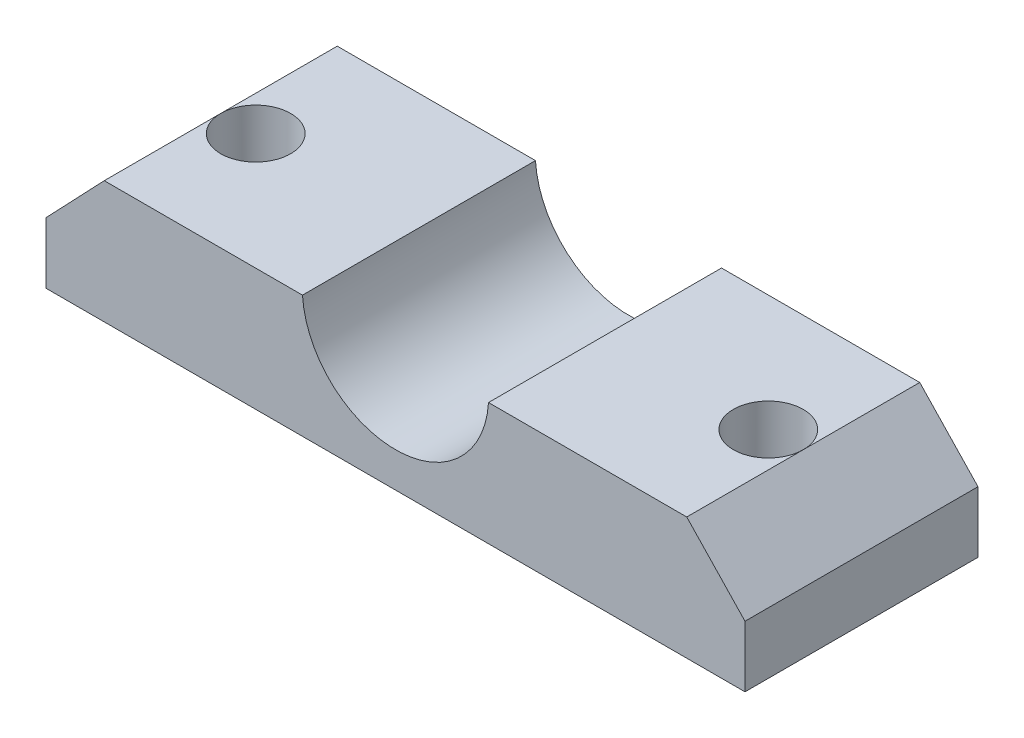
SolidWorks part; units mm, degrees
material "ABS"
ref_plane "Front Plane" through (0, 0, 0) normal (0, 0, 1) x (1, 0, 0)
ref_plane "Top Plane" through (0, 0, 0) normal (0, 1, 0) x (1, 0, 0)
ref_plane "Right Plane" through (0, 0, 0) normal (1, 0, 0) x (0, 0, -1)
sketch "Sketch1" plane through (0, 0, 0) normal (0, 0, 1) x (1, 0, 0)
  line L1 (-15, -5.5) -> (15, -5.5)
  line L2 (-15, -5.5) -> (-15, 5.5)
  line L3 (-15, 5.5) -> (15, 5.5)
  line L4 (15, -5.5) -> (15, 5.5)
  line L5 (-15, -5.5) -> (15, 5.5) construction
  line L6 (-15, 5.5) -> (15, -5.5) construction
  line L11 (-5, -5) -> (5, 5) construction
  line L12 (-5, 5) -> (5, -5) construction
  circle A0 centre (0, 0) radius 4
  point P0 (0, 0)
  point P6 (0, 0)
  dimension "D5" = 8
  dimension "D1" = 10
  dimension "D2" = 10
  dimension "D3" = 30
  dimension "D4" = 11
extrude "Boss-Extrude1" add sketch "Sketch1" along normal blind 10
sketch "Sketch2" plane through (0, 5.5, 0) normal (0, 1, 0) x (1, 0, 0)
  line L0 (0, 0) -> (0, -10)
  line L1 (15, -10) -> (-15, -10) construction
  line L2 (-11, -5) -> (11, -5)
  circle A0 centre (-11, -5) radius 1.5
  circle A1 centre (11, -5) radius 1.5
  point P8 (0, -5)
  dimension "D2" = 3
  dimension "D1" = 22
extrude "Cut-Extrude1" cut sketch "Sketch2" against normal blind 17
sketch "Sketch3" plane through (0, 0, 10) normal (0, 0, 1) x (1, 0, 0)
  line L0 (-15, 0) -> (15, 0)
  line L1 (15, -5.5) -> (15, 5.5) construction
  line L2 (-15, -0.25) -> (15, -0.25)
  line L3 (-15, 0.25) -> (15, 0.25)
  line L8 (15, -5.5) -> (15, 5.5)
  line L9 (15, 5.5) -> (-15, 5.5)
  line L10 (-15, 5.5) -> (-15, -5.5)
  line L11 (-15, -5.5) -> (15, -5.5)
  line L12 (15, -5.5) -> (15, 5.5)
  line L13 (15, 5.5) -> (-15, 5.5)
  line L14 (-15, 5.5) -> (-15, -5.5)
  line L15 (-15, -5.5) -> (15, -5.5)
  point P6 (0, 0)
  dimension "D1" = 0.25
  dimension "D2" = 0.25
  dimension "D3" = 0
extrude "Cut-Extrude2" cut sketch "Sketch3" against normal blind 17
sketch "Sketch4" plane through (0, 0, 10) normal (0, 0, 1) x (1, 0, 0)
  line L0 (11, 0) -> (-11, 0)
  line L1 (-11, 0) -> (-11, -5.5)
  line L2 (-15, -5.5) -> (15, -5.5) construction
  line L3 (11, 1.5) -> (-12.5, 1.5)
  line L4 (-12.5, 1.5) -> (-12.5, -5.5)
  line L5 (11, -1.5) -> (-9.5, -1.5)
  line L6 (-9.5, -1.5) -> (-9.5, -5.5)
  line L7 (-15, -5.5) -> (-15, -2.875)
  line L8 (-15, -0.25) -> (-15, -5.5) construction
  line L9 (-15, -2.875) -> (-12.5, -0.25)
  line L10 (0, 0) -> (0, -5.5)
  line L11 (15, -2.875) -> (12.5, -0.25)
  line L20 (15, -5.5) -> (15, -0.25)
  line L21 (15, -0.25) -> (3.9922, -0.25)
  line L25 (-3.9922, -0.25) -> (-15, -0.25)
  line L26 (-15, -0.25) -> (-15, -5.5)
  line L27 (-15, -5.5) -> (15, -5.5)
  line L28 (15, -5.5) -> (15, -0.25)
  line L29 (15, -0.25) -> (3.9922, -0.25)
  line L33 (-3.9922, -0.25) -> (-15, -0.25)
  line L34 (-15, -0.25) -> (-15, -5.5)
  line L35 (-15, -5.5) -> (15, -5.5)
  arc A1 (-3.9922, -0.25) -> (3.9922, -0.25) centre (0, 0) ccw
  arc A2 (-3.9922, -0.25) -> (3.9922, -0.25) centre (0, 0) ccw
  point P4 (0, 0)
  line M13 (15, -5.5) -> (15, -0.25)
  line M14 (15, -0.25) -> (3.9922, -0.25)
  line M18 (-3.9922, -0.25) -> (-15, -0.25)
  line M19 (-15, -0.25) -> (-15, -5.5)
  dimension "D1" = 22
  dimension "D2" = 1.5
  dimension "D3" = 1.5
  dimension "D4" = 0
extrude "Cut-Extrude3" cut sketch "Sketch4" against normal blind 17 contours L9 M19 M18 | L11 M13 M14
